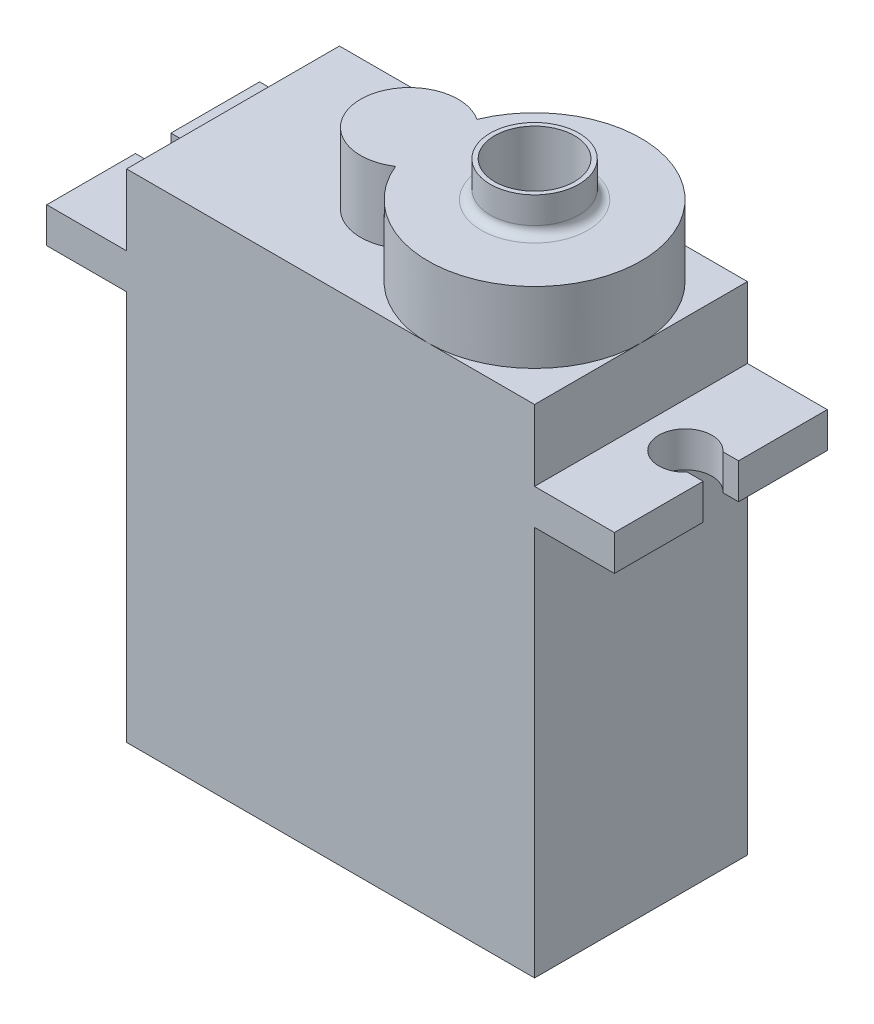
SolidWorks part; units mm, degrees
ref_plane "Front Plane" through (0, 0, 0) normal (0, 0, 1) x (1, 0, 0)
ref_plane "Top Plane" through (0, 0, 0) normal (0, 1, 0) x (1, 0, 0)
ref_plane "Right Plane" through (0, 0, 0) normal (1, 0, 0) x (0, 0, -1)
sketch "Sketch1" plane through (0, 0, 0) normal (0, 1, 0) x (1, 0, 0)
  line L1 (-11.5, 6) -> (11.5, 6)
  line L2 (-11.5, 6) -> (-11.5, -6)
  line L3 (-11.5, -6) -> (11.5, -6)
  line L4 (11.5, 6) -> (11.5, -6)
  line L5 (-11.5, 6) -> (11.5, -6) construction
  line L6 (-11.5, -6) -> (11.5, 6) construction
  point P0 (0, 0)
  dimension "D1" = 12
  dimension "D2" = 23
extrude "Boss-Extrude1" add sketch "Sketch1" along normal blind 22
sketch "Sketch2" plane through (0, 22, 0) normal (0, 1, 0) x (1, 0, 0)
  line L0 (11.5, 6) -> (-11.5, 6) construction
  line L1 (-16, 6) -> (16, 6)
  line L2 (-16, 6) -> (-16, -6)
  line L3 (-16, -6) -> (16, -6)
  line L4 (16, 6) -> (16, -6)
  line L5 (-16, 6) -> (16, -6) construction
  line L6 (-16, -6) -> (16, 6) construction
  point P1 (0, 0)
  dimension "D1" = 0
  dimension "D2" = 16
extrude "Boss-Extrude2" add sketch "Sketch2" along normal blind 2
sketch "Sketch3" plane through (0, 24, 0) normal (0, 1, 0) x (1, 0, 0)
  line L0 (-16, -6) -> (16, -6) construction
  line L1 (-11.5, 6) -> (11.5, 6)
  line L2 (-11.5, 6) -> (-11.5, -6)
  line L3 (-11.5, -6) -> (11.5, -6)
  line L4 (11.5, 6) -> (11.5, -6)
  line L5 (-11.5, 6) -> (11.5, -6) construction
  line L6 (-11.5, -6) -> (11.5, 6) construction
  point P0 (0, 0)
  dimension "D1" = 23
sketch "Sketch4" plane through (0, 24, 0) normal (0, 1, 0) x (1, 0, 0)
  line L0 (-16.6395, 1) -> (-15.118, 1)
  line L1 (-16.6395, -1) -> (-15.118, -1)
  line L2 (-16.6395, 1) -> (-16.6395, -1)
  line L3 (15.118, 1) -> (17.1213, 1)
  line L4 (17.1213, 1) -> (17.1213, -1)
  line L5 (17.1213, -1) -> (15.118, -1)
  arc A0 (-15.118, -1) -> (-15.118, 1) centre (-14, 0) ccw
  arc A1 (15.118, 1) -> (15.118, -1) centre (14, 0) ccw
  dimension "D3" = 3
  dimension "D4" = 3
  dimension "D1" = 28
  dimension "D2" = 14
  dimension "D5" = 1
  dimension "D6" = 1
extrude "Cut-Extrude1" cut sketch "Sketch4" against normal blind 5
extrude "Boss-Extrude4" add sketch "Sketch3" along normal blind 4
sketch "Sketch5" plane through (0, 28, 0) normal (0, 1, 0) x (1, 0, 0)
  line L1 (11.5, -6) -> (11.5, 6) construction
  line L2 (11.5, 6) -> (-11.5, 6) construction
  line L3 (-11.5, -6) -> (11.5, -6) construction
  arc A0 (-0.0432, -2.2962) -> (-0.0432, 2.2962) centre (5.5, 0) ccw
  arc A2 (-0.0432, 2.2962) -> (-0.0432, -2.2962) centre (-1.5565, 0) ccw
  dimension "D1" = 5.5
extrude "Boss-Extrude5" add sketch "Sketch5" along normal blind 4
sketch "Sketch6" plane through (0, 32, 0) normal (0, 1, 0) x (1, 0, 0)
  circle A0 centre (5.5, 0) radius 2.25
  arc A1 (-0.0432, -2.2962) -> (-0.0432, 2.2962) centre (5.5, 0) ccw construction
  circle A2 centre (5.5, 0) radius 2.5
  dimension "D2" = 4.5
  dimension "D3" = 5
  dimension "D1" = 0
extrude "Boss-Extrude6" add sketch "Sketch6" along normal blind 2
sketch "Sketch7" plane through (0, 32, 0) normal (0, 1, 0) x (1, 0, 0)
  circle A0 centre (5.5, 0) radius 2.25
extrude "Cut-Extrude2" cut sketch "Sketch7" against normal blind 4
fillet "Fillet4" radius 0.5 1 edges at (5.5, 32, 2.5)
sketch "Sketch8" plane through (0, 0, -6) normal (0, 0, -1) x (-1, 0, 0)
  line L0 (-11.5, 0) -> (11.5, 0) construction
  line L1 (-11.5, 22) -> (-11.5, 0) construction
  circle A0 centre (-5.5, 6) radius 2.25
  dimension "D1" = 4.5
  dimension "D2" = 6
  dimension "D3" = 6
extrude "Boss-Extrude7" add sketch "Sketch8" along normal blind 1
sketch "Sketch9" plane through (0, 0, -7) normal (0, 0, -1) x (-1, 0, 0)
  circle A0 centre (-5.5, 6) radius 0.75
  dimension "D1" = 1.5
extrude "Boss-Extrude8" add sketch "Sketch9" along normal blind 2
